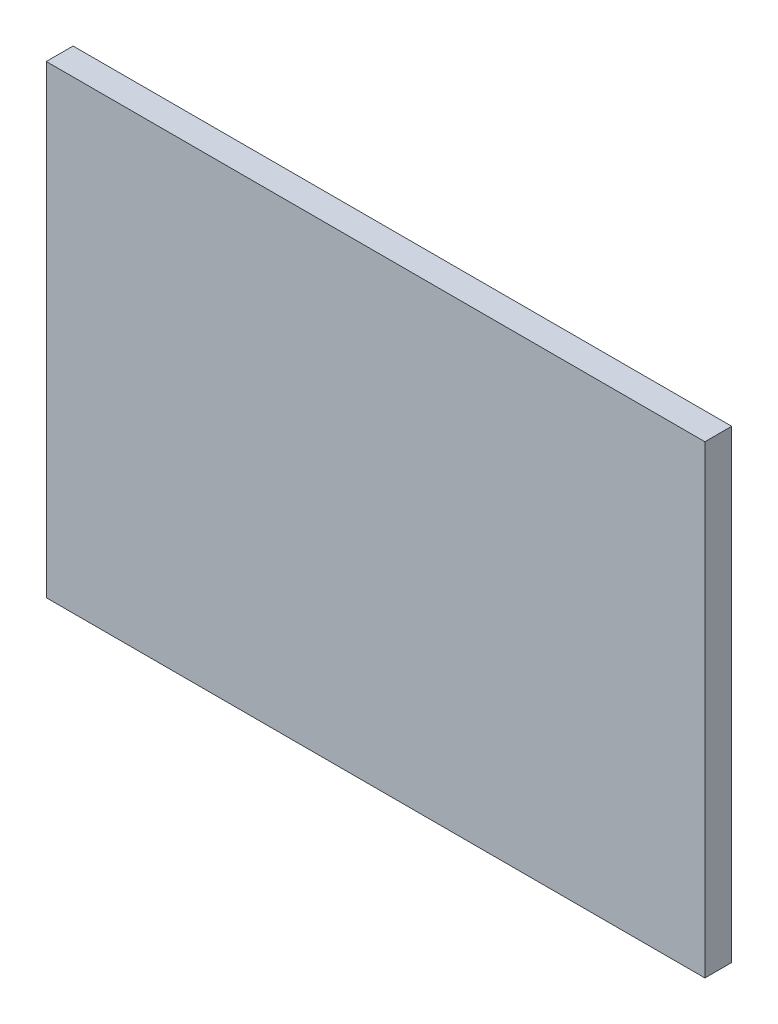
SolidWorks part; units mm, degrees
ref_plane "Front Plane" through (0, 0, 0) normal (0, 0, 1) x (1, 0, 0)
ref_plane "Top Plane" through (0, 0, 0) normal (0, 1, 0) x (1, 0, 0)
ref_plane "Right Plane" through (0, 0, 0) normal (1, 0, 0) x (0, 0, -1)
sketch "Sketch1" plane through (0, 0, 0) normal (0, 0, 1) x (1, 0, 0)
  line L1 (-19.5, -13.75) -> (19.5, -13.75)
  line L2 (-19.5, -13.75) -> (-19.5, 13.75)
  line L3 (-19.5, 13.75) -> (19.5, 13.75)
  line L4 (19.5, -13.75) -> (19.5, 13.75)
  line L5 (0, 13.75) -> (0, -13.75) construction
  line L6 (-19.5, 0) -> (19.5, 0) construction
  point P0 (0, 0)
  dimension "D1" = 39
  dimension "D2" = 27.5
extrude "Boss-Extrude1" add sketch "Sketch1" along normal blind 1.5875
